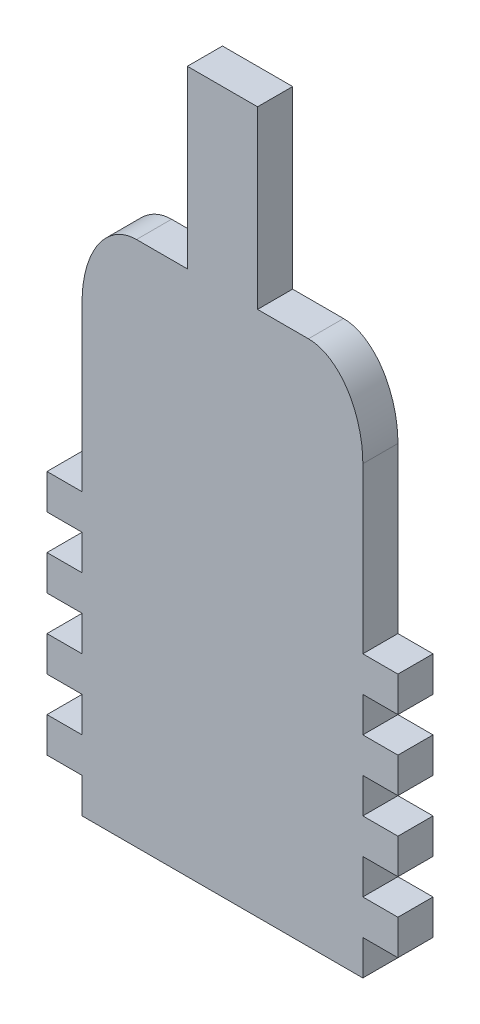
SolidWorks part; units mm, degrees
ref_plane "Plan de face" through (0, 0, 0) normal (0, 0, 1) x (1, 0, 0)
ref_plane "Plan de dessus" through (0, 0, 0) normal (0, 1, 0) x (1, 0, 0)
ref_plane "Plan de droite" through (0, 0, 0) normal (1, 0, 0) x (0, 0, -1)
sketch "Esquisse1" plane through (0, 0, 0) normal (0, 0, 1) x (1, 0, 0)
  line L29 (-88.4214, 20.835) -> (-88.4214, 25.835)
  line L30 (-93.4214, 25.835) -> (-88.4214, 25.835)
  line L31 (-93.4214, 25.835) -> (-93.4214, 30.835)
  line L32 (-93.4214, 30.835) -> (-88.4214, 30.835)
  line L33 (-88.4214, 30.835) -> (-88.4214, 35.835)
  line L34 (-93.4214, 35.835) -> (-88.4214, 35.835)
  line L35 (-93.4214, 35.835) -> (-93.4214, 40.835)
  line L36 (-93.4214, 40.835) -> (-88.4214, 40.835)
  line L37 (-88.4214, 40.835) -> (-88.4214, 45.835)
  line L38 (-93.4214, 45.835) -> (-88.4214, 45.835)
  line L39 (-93.4214, 45.835) -> (-93.4214, 50.835)
  line L40 (-93.4214, 50.835) -> (-88.4214, 50.835)
  line L43 (-73.4214, 95.835) -> (-73.4214, 120.835)
  line L47 (-80.6714, 95.835) -> (-73.4214, 95.835)
  line L48 (-73.4214, 120.835) -> (-63.4214, 120.835)
  line L49 (-88.4214, 20.835) -> (-48.4214, 20.835)
  line L50 (-56.1714, 95.835) -> (-63.4214, 95.835)
  line L52 (-63.4214, 95.835) -> (-63.4214, 120.835)
  line L53 (-43.4214, 50.835) -> (-48.4214, 50.835)
  line L54 (-43.4214, 45.835) -> (-43.4214, 50.835)
  line L55 (-43.4214, 45.835) -> (-48.4214, 45.835)
  line L56 (-48.4214, 40.835) -> (-48.4214, 45.835)
  line L57 (-43.4214, 40.835) -> (-48.4214, 40.835)
  line L58 (-43.4214, 35.835) -> (-43.4214, 40.835)
  line L59 (-43.4214, 35.835) -> (-48.4214, 35.835)
  line L60 (-48.4214, 30.835) -> (-48.4214, 35.835)
  line L61 (-43.4214, 30.835) -> (-48.4214, 30.835)
  line L62 (-43.4214, 25.835) -> (-43.4214, 30.835)
  line L63 (-43.4214, 25.835) -> (-48.4214, 25.835)
  line L64 (-48.4214, 20.835) -> (-48.4214, 25.835)
  line L65 (-88.4214, 55.835) -> (-93.4214, 55.835)
  line L66 (-93.4214, 55.835) -> (-93.4214, 60.835)
  line L67 (-93.4214, 60.835) -> (-88.4214, 60.835)
  line L68 (-88.4214, 50.835) -> (-88.4214, 55.835)
  line L69 (-88.4214, 60.835) -> (-88.4214, 84.2888)
  line L70 (-68.4214, 120.835) -> (-68.4214, 20.835) construction
  line L71 (-43.4214, 60.835) -> (-48.4214, 60.835)
  line L72 (-43.4214, 55.835) -> (-43.4214, 60.835)
  line L73 (-48.4214, 55.835) -> (-43.4214, 55.835)
  line L74 (-48.4214, 50.835) -> (-48.4214, 55.835)
  line L75 (-48.4214, 60.835) -> (-48.4214, 84.2888)
  ellipse E0 centre (-80.6714, 84.2888) end of major axis (-80.6714, 72.7426) minor radius 7.75 (-80.6714, 95.835) -> (-88.4214, 84.2888) ccw
  ellipse E1 centre (-56.1714, 84.2888) end of major axis (-56.1714, 72.7426) minor radius 7.75 (-56.1714, 95.835) -> (-48.4214, 84.2888) cw
  dimension "D1" = 5
  dimension "D2" = 75
  dimension "D3" = 5
  dimension "D4" = 5
  dimension "D5" = 75
  dimension "D6" = 5
  dimension "D7" = 5
extrude "Boss.-Extru.1" add sketch "Esquisse1" along normal blind 5
